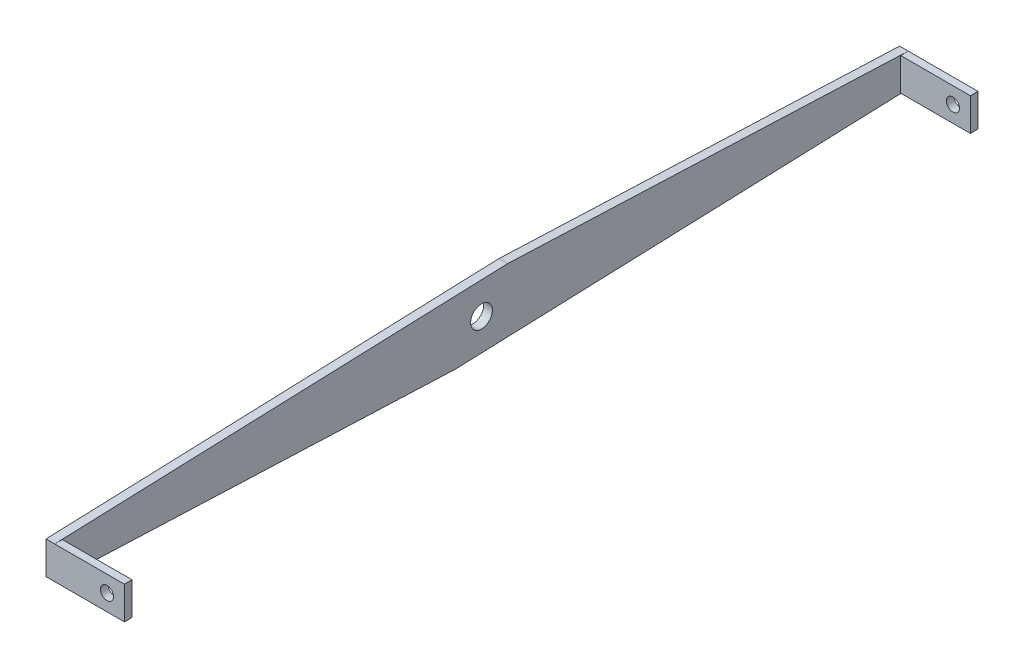
SolidWorks part; units mm, degrees
ref_plane "Front Plane" through (0, 0, 0) normal (0, 0, 1) x (1, 0, 0)
ref_plane "Top Plane" through (0, 0, 0) normal (0, 1, 0) x (1, 0, 0)
ref_plane "Right Plane" through (0, 0, 0) normal (1, 0, 0) x (0, 0, -1)
sketch "Sketch2" plane through (0, 0, 0) normal (1, 0, 0) x (0, 0, -1)
  line L0 (0, 0) -> (208, 7.5)
  line L2 (0, 0) -> (0, -15)
  line L4 (392, 0) -> (392, -15)
  line L5 (208, 7.5) -> (392, 0)
  line L6 (0, -15) -> (184, -22.5)
  line L7 (184, -22.5) -> (392, -15)
  dimension "D1" = 15
  dimension "D2" = 392
extrude "Boss-Extrude2" add sketch "Sketch2" along normal mid plane 4
sketch "Sketch4" plane through (2, 0, 0) normal (1, 0, 0) x (0, 0, -1)
  line L1 (0, 0) -> (3.5, 0)
  line L2 (0, 0) -> (0, -15)
  line L3 (0, -15) -> (3.5, -15)
  line L4 (3.5, 0) -> (3.5, -15)
  line L5 (392, -15) -> (388.5, -15)
  line L6 (392, -15) -> (392, 0)
  line L7 (392, 0) -> (388.5, 0)
  line L8 (388.5, -15) -> (388.5, 0)
  dimension "D1" = 15
  dimension "D2" = 3.5
  dimension "D3" = 15
  dimension "D4" = 3.5
extrude "Boss-Extrude3" add sketch "Sketch4" along normal blind 32
sketch "Sketch5" plane through (0, 0, 0) normal (0, 0, 1) x (1, 0, 0)
  line L1 (34, -15) -> (2, -15) construction
  line L2 (34, 0) -> (34, -15) construction
  circle A0 centre (26, -7.5) radius 3
  dimension "D1" = 70
  dimension "D2" = 7.5
  dimension "D3" = 8
extrude "Cut-Extrude1" cut sketch "Sketch5" against normal blind 392
sketch "Sketch7" plane through (-2, 0, 0) normal (-1, 0, 0) x (0, 0, 1)
  line L0 (0, 0) -> (0, -15) construction
  circle A0 centre (-196, -7.5) radius 5
  dimension "D1" = 196
extrude "Cut-Extrude2" cut sketch "Sketch7" against normal blind 5
